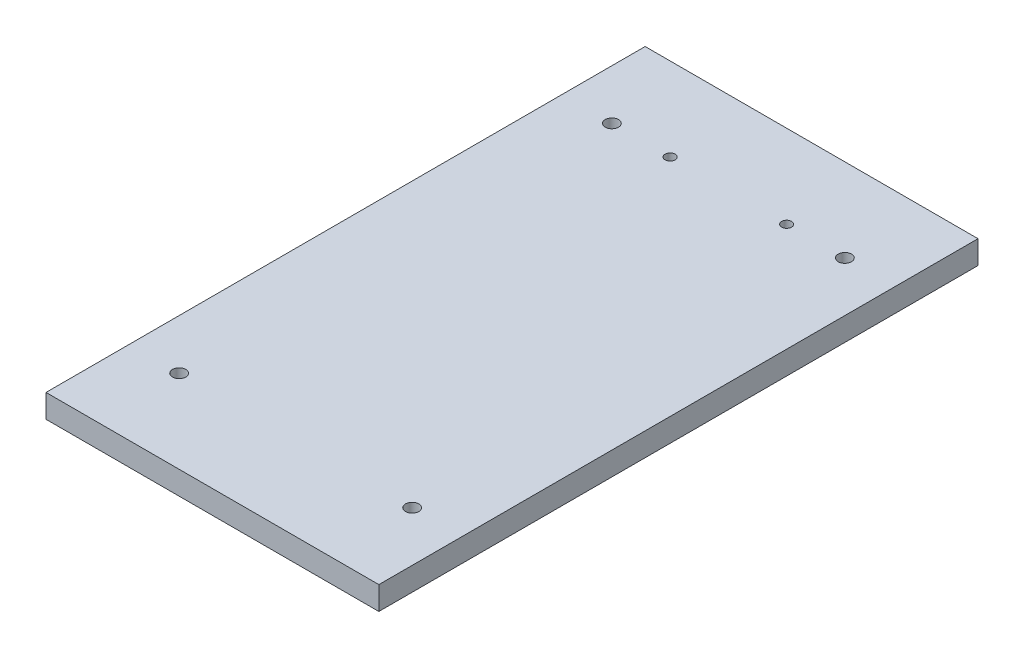
SolidWorks part; units mm, degrees
ref_plane "Front Plane" through (0, 0, 0) normal (0, 0, 1) x (1, 0, 0)
ref_plane "Top Plane" through (0, 0, 0) normal (0, 1, 0) x (1, 0, 0)
ref_plane "Right Plane" through (0, 0, 0) normal (1, 0, 0) x (0, 0, -1)
sketch "Sketch1" plane through (0, 0, 0) normal (0, 1, 0) x (1, 0, 0)
  line L1 (0, 0) -> (100, 0)
  line L2 (0, 0) -> (0, 180)
  line L3 (0, 180) -> (100, 180)
  line L4 (100, 0) -> (100, 180)
  dimension "D1" = 100
  dimension "D2" = 180
extrude "Boss-Extrude1" add sketch "Sketch1" along normal blind 7
sketch "Sketch3" plane through (0, 7, 0) normal (0, 1, 0) x (1, 0, 0)
  line L0 (0, 0) -> (100, 0) construction
  line L1 (0, 180) -> (0, 0) construction
  circle A0 centre (15, 25) radius 2
  circle A1 centre (85, 25) radius 2
  circle A2 centre (15, 155) radius 2
  circle A3 centre (85, 155) radius 2
  dimension "D1" = 4
  dimension "D2" = 25
  dimension "D3" = 15
  dimension "D4" = 2
  dimension "D5" = 2
extrude "Cut-Extrude1" cut sketch "Sketch3" against normal through all
sketch "Sketch4" plane through (0, 7, 0) normal (0, 1, 0) x (1, 0, 0)
  line L0 (0, 180) -> (0, 0) construction
  line L1 (100, 180) -> (0, 180) construction
  circle A0 centre (32.5, 155) radius 1.5
  circle A1 centre (67.5, 155) radius 1.5
  dimension "D1" = 3
  dimension "D2" = 32.5
  dimension "D3" = 25
  dimension "D4" = 2
extrude "Cut-Extrude2" cut sketch "Sketch4" against normal through all
